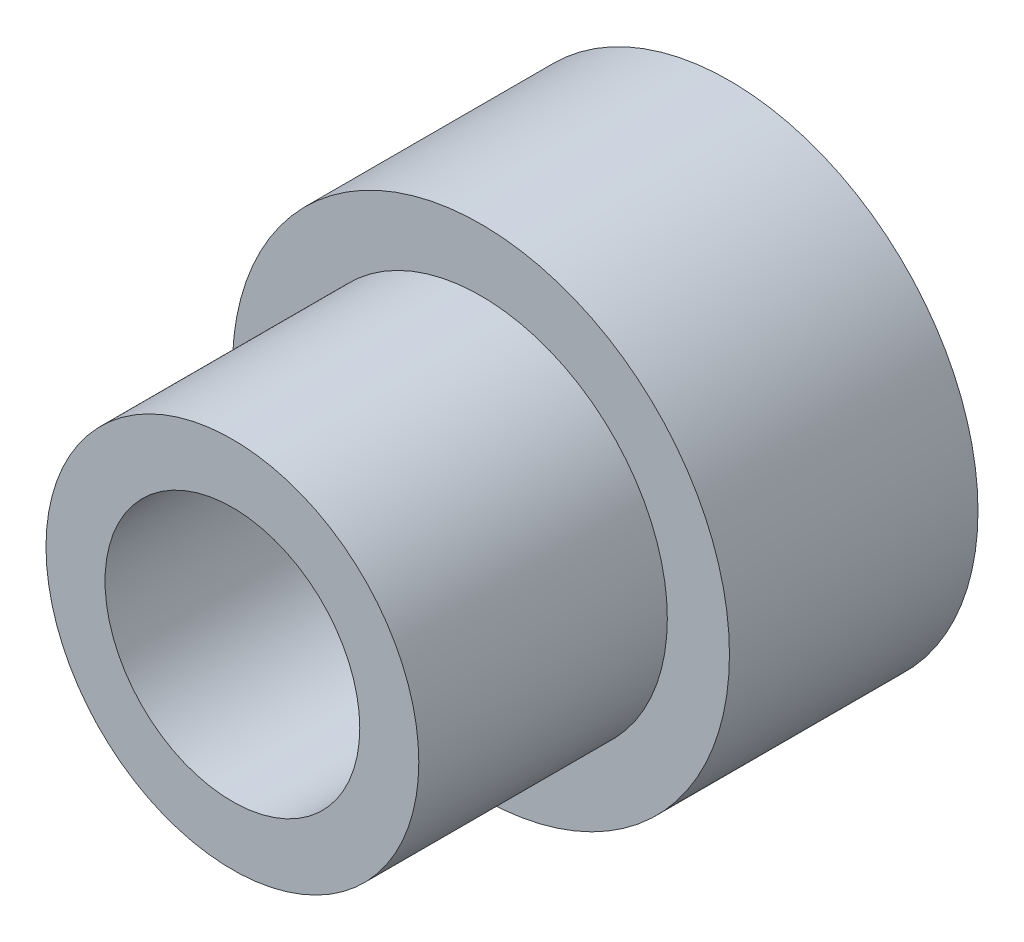
SolidWorks part; units mm, degrees
ref_plane "Alzado" through (0, 0, 0) normal (0, 0, 1) x (1, 0, 0)
ref_plane "Planta" through (0, 0, 0) normal (0, 1, 0) x (1, 0, 0)
ref_plane "Vista lateral" through (0, 0, 0) normal (1, 0, 0) x (0, 0, -1)
sketch "Croquis1" plane through (0, 0, 0) normal (0, 0, 1) x (1, 0, 0)
  circle A0 centre (0, 0) radius 2
  dimension "D1" = 4
extrude "Saliente-Extruir1" add sketch "Croquis1" along normal blind 2
sketch "Croquis2" plane through (0, 0, 2) normal (0, 0, 1) x (1, 0, 0)
  circle A0 centre (0, 0) radius 1.5
  circle A1 centre (0, 0) radius 1.025
  dimension "D1" = 3
  dimension "D2" = 2.05
extrude "Saliente-Extruir2" add sketch "Croquis2" along normal blind 2
chamfer "Chaflán1" distance 0.2 angle 45 1 edges at (1.025, 0, 2)
